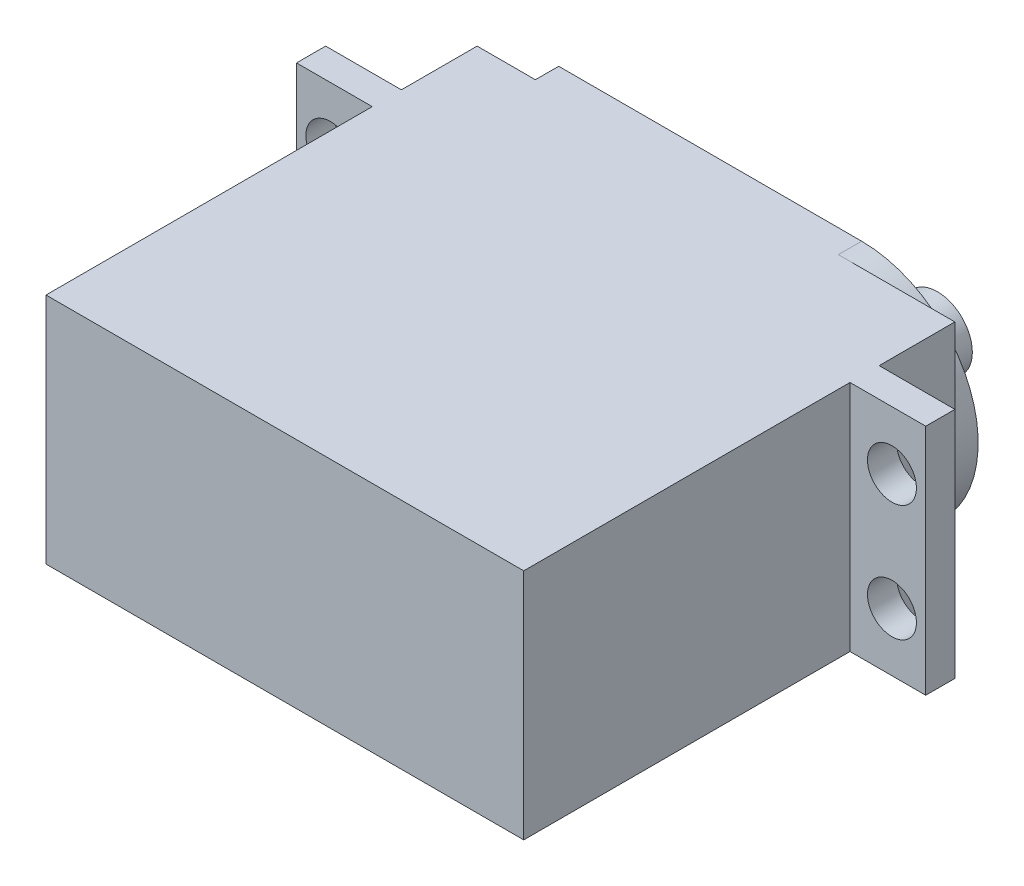
SolidWorks part; units mm, degrees
ref_plane "前视基准面" through (0, 0, 0) normal (0, 0, 1) x (1, 0, 0)
ref_plane "上视基准面" through (0, 0, 0) normal (0, 1, 0) x (1, 0, 0)
ref_plane "右视基准面" through (0, 0, 0) normal (1, 0, 0) x (0, 0, -1)
ref_plane "基准面4" through (0, -50, 0) normal (0, -1, 0) x (1, 0, 0)
sketch "草图1" plane through (0, -50, 0) normal (0, -1, 0) x (1, 0, 0)
  line L0 (27, -15.5) -> (27, 23.5)
  line L1 (27, 23.5) -> (-27, 23.5)
  line L2 (-27, 23.5) -> (-27, -15.5)
  line L3 (-27, -15.5) -> (27, -15.5)
extrude "凸台-拉伸1" add sketch "草图1" against normal blind 20
sketch "草图2" plane through (0, -30, 0) normal (0, 1, 0) x (-1, 0, 0)
  line L0 (-27, -4.5) -> (-20.5, -4.5)
  line L1 (-20.5, -4.5) -> (-20.5, 23.5)
  line L2 (-20.5, 23.5) -> (-27, 23.5)
  line L3 (-27, 23.5) -> (-27, -4.5)
extrude "切除-拉伸1" cut sketch "草图2" against normal through all
sketch "草图3" plane through (0, -30, 0) normal (0, 1, 0) x (-1, 0, 0)
  line L0 (20.5, 23.5) -> (20.5, -4.5)
  line L1 (20.5, -4.5) -> (27, -4.5)
  line L2 (27, -4.5) -> (27, 23.5)
  line L3 (27, 23.5) -> (20.5, 23.5)
extrude "切除-拉伸2" cut sketch "草图3" against normal through all
sketch "草图4" plane through (0, -30, 0) normal (0, 1, 0) x (-1, 0, 0)
  line L0 (27, -7) -> (20.5, -7)
  line L1 (20.5, -7) -> (20.5, -15.5)
  line L2 (20.5, -15.5) -> (27, -15.5)
  line L3 (27, -15.5) -> (27, -7)
extrude "切除-拉伸3" cut sketch "草图4" against normal through all
sketch "草图5" plane through (0, -30, 0) normal (0, 1, 0) x (-1, 0, 0)
  line L0 (20.5, -13.5) -> (15.5, -13.5)
  line L1 (15.5, -13.5) -> (15.5, -15.5)
  line L2 (15.5, -15.5) -> (20.5, -15.5)
  line L3 (20.5, -15.5) -> (20.5, -13.5)
extrude "切除-拉伸4" cut sketch "草图5" against normal through all
sketch "草图6" plane through (0, 0, -15.5) normal (0, 0, -1) x (-1, 0, 0)
  line L0 (-10.5, -30) -> (-27, -30)
  line L1 (-27, -30) -> (-27, -50)
  line L2 (-27, -50) -> (-10.5, -50)
  arc A0 (-10.5, -50) -> (-10.5, -30) centre (-10.5, -40) cw
extrude "切除-拉伸5" cut sketch "草图6" against normal blind 2
sketch "草图7" plane through (0, -30, 0) normal (0, 1, 0) x (-1, 0, 0)
  line L0 (-27, -13.5) -> (-20.5, -13.5)
  line L1 (-20.5, -13.5) -> (-20.5, -7)
  line L2 (-20.5, -7) -> (-27, -7)
  line L3 (-27, -7) -> (-27, -13.5)
extrude "切除-拉伸6" cut sketch "草图7" against normal through all
ref_plane "基准面5" through (0, -40, 0) normal (0, 1, 0) x (1, 0, 0)
sketch "草图8" plane through (0, -40, 0) normal (0, 1, 0) x (1, 0, 0)
  line L0 (13.5, 22) -> (10.5, 22)
  line L1 (10.5, 22) -> (10.5, 15.5)
  line L2 (10.5, 15.5) -> (17, 15.5)
  line L3 (17, 15.5) -> (17, 17)
  line L4 (17, 17) -> (13.5, 17)
  line L5 (13.5, 17) -> (13.5, 22)
  line L6 (10.5, 22) -> (10.5, 15.5) construction
revolve "旋转1" add sketch "草图8" angle 360 about L6
hole_wizard "Ø4.2 (4.2) 直径孔1" positions "草图10" profile "草图9" hole size "Ø4.2" standard "ANSI Metric"
sketch "草图10" plane through (0, 0, -7) normal (0, 0, -1) x (-1, 0, 0)
  point P0 (24.1, -45)
  point P1 (24.1, -35)
  point P2 (-24.1, -45)
  point P3 (-24.1, -35)
sketch "草图9" plane through (-24.1, -45, -7) normal (1, 0, 0) x (0, 1, 0)
  line L0 (0, 0) -> (0, 30.5)
  line L1 (0, 30.5) -> (2.1, 30.5)
  line L2 (2.1, 30.5) -> (2.1, 0)
  line L5 (2.1, 0) -> (0, 0)
  line L11 (0, -6.35) -> (0, 107.95) construction
  dimension "通孔孔直径" = 4.2
  dimension "通孔孔深度" = 30.5
